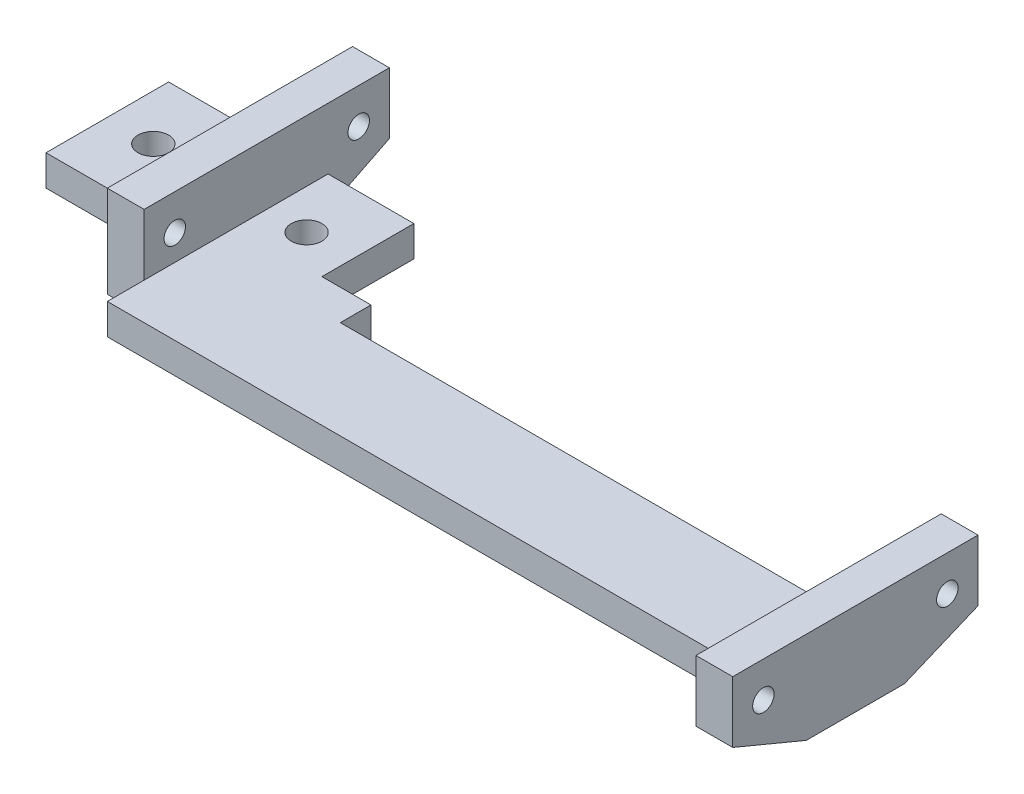
SolidWorks part; units mm, degrees
ref_plane "前视基准面" through (0, 0, 0) normal (0, 0, 1) x (1, 0, 0)
ref_plane "上视基准面" through (0, 0, 0) normal (0, 1, 0) x (1, 0, 0)
ref_plane "右视基准面" through (0, 0, 0) normal (1, 0, 0) x (0, 0, -1)
sketch "草图1" plane through (0, 0, 0) normal (0, 1, 0) x (1, 0, 0)
  line L0 (0, 0) -> (0, 20)
  line L1 (0, 20) -> (-20, 20)
  line L3 (-20, -16) -> (100, -16)
  line L4 (100, -16) -> (100, 0)
  line L5 (100, 0) -> (0, 0)
  line L7 (-20, 20) -> (-20, -16)
  dimension "D1" = 20
  dimension "D2" = 20
  dimension "D3" = 16
  dimension "D4" = 100
extrude "凸台-拉伸1" add sketch "草图1" along normal blind 5
sketch "草图2" plane through (100, 0, 0) normal (1, 0, 0) x (0, 0, -1)
  line L0 (-16, 0) -> (-28, 5)
  line L1 (-28, 5) -> (-28, 15)
  line L2 (-28, 15) -> (12, 15)
  line L3 (12, 15) -> (12, 5)
  line L4 (0, 5) -> (20, 5) construction
  line L5 (12, 5) -> (0, 0)
  line L6 (-8, 15) -> (-8, 0) construction
  line L7 (-16, 0) -> (0, 0) construction
  line L8 (-23, 9.2) -> (7, 9.2) construction
  line L9 (-16, 5) -> (0, 5) construction
  line L10 (-16, 0) -> (0, 0)
  circle A0 centre (-23, 9.2) radius 1.75
  circle A1 centre (7, 9.2) radius 1.75
  point P18 (-8, 9.2)
  dimension "D3" = 3.5
  dimension "D1" = 40
  dimension "D2" = 10
  dimension "D4" = 30
  dimension "D5" = 4.2
extrude "凸台-拉伸2" add sketch "草图2" against normal blind 6
sketch "草图3" plane through (-20, 0, 0) normal (-1, 0, 0) x (0, 0, 1)
  line L1 (-20, 5) -> (0, 5)
  line L2 (-20, 5) -> (-20, 0)
  line L3 (-20, 0) -> (0, 0)
  line L4 (0, 5) -> (0, 0)
  line L7 (-20, 0) -> (16, 0) construction
extrude "凸台-拉伸3" add sketch "草图3" along normal offset from surface (20 mm away) 40 up to face at (0, 2.5, -10)
sketch "草图4" plane through (0, 5, 0) normal (0, 1, 0) x (1, 0, 0)
  line L0 (-7.5, 10) -> (-32.5, 10) construction
  line L1 (-20, 10) -> (-20, 20) construction
  line L2 (0, 20) -> (-40, 20) construction
  line L3 (-40, 0) -> (-40, 20) construction
  circle A0 centre (-32.5, 10) radius 2.5
  circle A2 centre (-7.5, 10) radius 2.5
  point P11 (-40, 10)
  dimension "D2" = 5
  dimension "D1" = 25
extrude "切除-拉伸1" cut sketch "草图4" against normal through all
sketch "草图5" plane through (0, 5, 0) normal (0, 1, 0) x (1, 0, 0)
  line L1 (-20, 30) -> (-14, 30)
  line L2 (-20, 30) -> (-20, -10)
  line L3 (-20, -10) -> (-14, -10)
  line L4 (-14, 30) -> (-14, -10)
  line L5 (-20, 10) -> (-40, 10) construction
  line L6 (-40, 0) -> (-40, 20) construction
  line L8 (0, 20) -> (-40, 20) construction
  point P10 (-20, 20)
  dimension "D1" = 6
  dimension "D2" = 40
extrude "凸台-拉伸4" add sketch "草图5" along normal blind 10
sketch "草图7" plane through (-20, 0, 0) normal (-1, 0, 0) x (0, 0, 1)
  line L0 (-30, 5) -> (-20, 0)
  line L1 (-20, 0) -> (-20, 5)
  line L2 (-20, 5) -> (-30, 5)
extrude "凸台-拉伸5" add sketch "草图7" against normal up to surface (6 mm away) up to face at (-14, 9, -12)
sketch "草图8" plane through (-20, 0, 0) normal (-1, 0, 0) x (0, 0, 1)
  line L0 (-25, 9.2) -> (5, 9.2) construction
  line L1 (-10, 9.2) -> (-10, 15) construction
  line L2 (-30, 15) -> (10, 15) construction
  line L3 (-20, 5) -> (0, 5) construction
  circle A0 centre (-25, 9.2) radius 1.75
  circle A1 centre (5, 9.2) radius 1.75
  dimension "D3" = 3.5
  dimension "D1" = 30
  dimension "D2" = 4.2
extrude "切除-拉伸2" cut sketch "草图8" against normal up to next
sketch "草图13" plane through (94, 0, 0) normal (-1, 0, 0) x (0, 0, 1)
  line L0 (-12, 5) -> (28, 5)
  line L1 (28, 5) -> (16, 0)
  line L2 (16, 0) -> (0, 0)
  line L3 (0, 0) -> (-12, 5)
extrude "凸台-拉伸6" add sketch "草图13" along normal blind 10
ref_plane "基准面1" through (41.7049, 0, -34.7541) normal (0.7682, 0, -0.6402) x (-0.6402, 0, -0.7682)
sketch "草图14" plane through (41.7049, 0, -34.7541) normal (0.7682, 0, -0.6402) x (-0.6402, 0, -0.7682)
  line L0 (-66.067, 5) -> (-66.067, 0)
  line L1 (-66.067, 0) -> (-81.6875, 5)
  line L2 (-81.6875, 5) -> (-66.067, 5)
extrude "切除-拉伸3" cut sketch "草图14" against normal up to next
ref_plane "基准面2" through (49.5738, 0, 41.3115) normal (0.7682, 0, 0.6402) x (0.6402, 0, -0.7682)
sketch "草图15" plane through (49.5738, 0, 41.3115) normal (0.7682, 0, 0.6402) x (0.6402, 0, -0.7682)
  line L0 (69.396, 5) -> (53.7755, 0)
  line L1 (53.7755, 0) -> (53.7755, 5)
  line L2 (53.7755, 5) -> (69.396, 5)
extrude "切除-拉伸4" cut sketch "草图15" against normal up to next
sketch "草图16" plane through (0, 5, 0) normal (0, 1, 0) x (1, 0, 0)
  line L0 (-20, -10) -> (-14, -10)
  line L1 (-14, -10) -> (-14, -16)
  line L2 (-20, -16) -> (84, -16) construction
  line L3 (-14, -16) -> (-20, -16)
  line L4 (-20, -16) -> (-20, -10)
extrude "切除-拉伸5" cut sketch "草图16" against normal blind 10
sketch "草图17" plane through (0, 0, 0) normal (0, 0, -1) x (-1, 0, 0)
  line L0 (-84, 0) -> (0, 0) construction
  line L1 (0, 5) -> (-8, 5)
  line L2 (0, 5) -> (0, 0)
  line L3 (0, 0) -> (-8, 0)
  line L4 (-8, 5) -> (-8, 0)
  dimension "D1" = 8
extrude "凸台-拉伸7" add sketch "草图17" along normal blind 5
